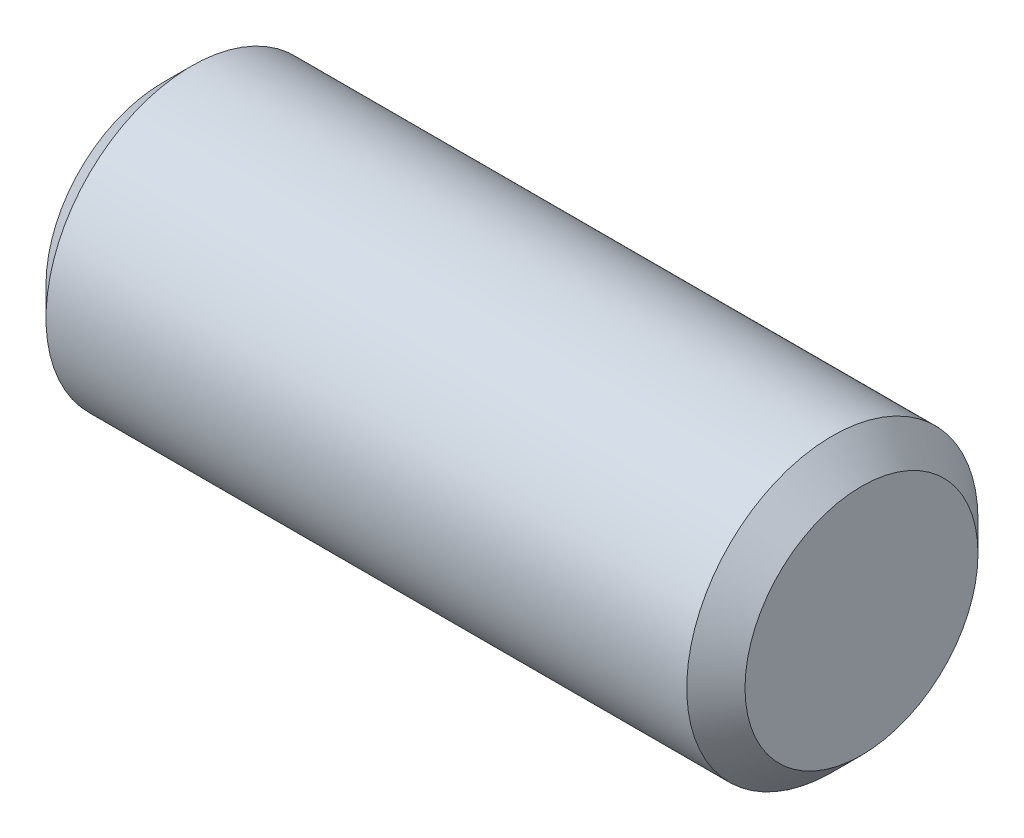
SolidWorks part; units mm, degrees
ref_plane "Front Plane" through (0, 0, 0) normal (0, 0, 1) x (1, 0, 0)
ref_plane "Top Plane" through (0, 0, 0) normal (0, 1, 0) x (1, 0, 0)
ref_plane "Right Plane" through (0, 0, 0) normal (1, 0, 0) x (0, 0, -1)
sketch "Sketch1" plane through (0, 0, 0) normal (1, 0, 0) x (0, 0, -1)
  line L0 (-6, 0) -> (6, 0) construction
  line L1 (0, 2.5) -> (0, -2.5) construction
  circle A0 centre (0, 0) radius 2.5 construction
  point P4 (0, 0)
  point P5 (0, 0)
  dimension "Diameter" = 5
  dimension "Length" = 12
sketch "Sketch2" plane through (0, 0, 0) normal (1, 0, 0) x (0, 0, -1)
  circle A1 centre (0, 0) radius 2.5 construction
  circle A2 centre (0, 0) radius 2.5
extrude "Boss-Extrude1" add sketch "Sketch2" against normal mid plane 12
chamfer "Chamfer2" distance 0.5 angle 45 2 edges at (-6, 0, -2.5) (6, 0, -2.5)
equation "\"D1@Chamfer2\"=\"Diameter@Sketch1\"*.1"
equation "\"D1@Boss-Extrude1\"=\"Length@Sketch1\""
